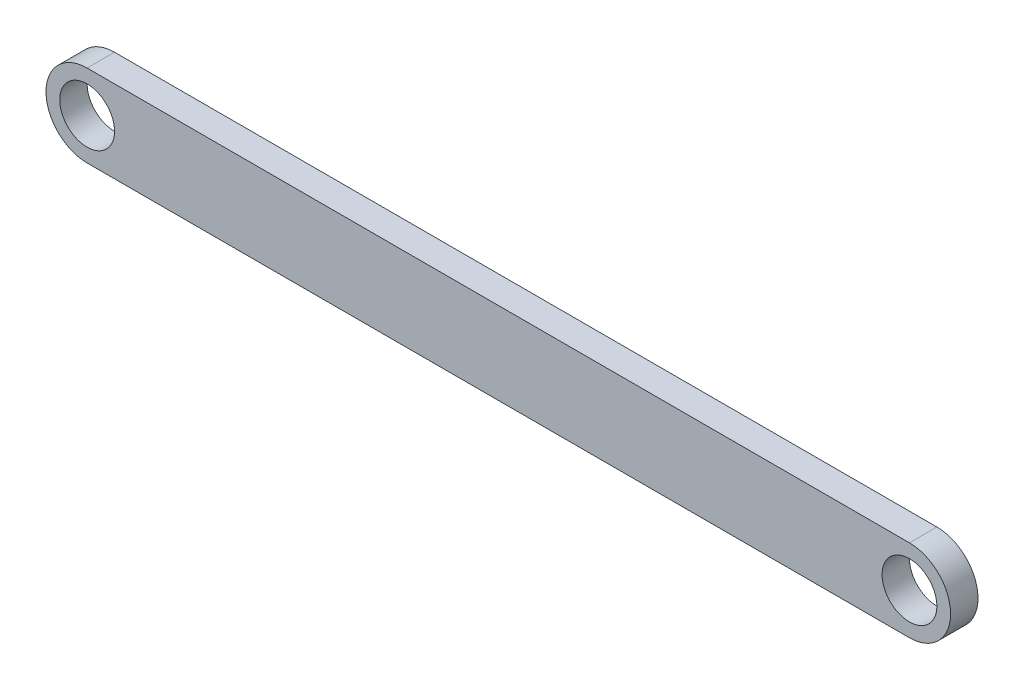
SolidWorks part; units mm, degrees
ref_plane "Ön Düzlem" through (0, 0, 0) normal (0, 0, 1) x (1, 0, 0)
ref_plane "Üst Düzlem" through (0, 0, 0) normal (0, 1, 0) x (1, 0, 0)
ref_plane "Sağ Düzlem" through (0, 0, 0) normal (1, 0, 0) x (0, 0, -1)
sketch "Çizim1" plane through (0, 0, 0) normal (0, 0, 1) x (1, 0, 0)
  line L0 (-43.2944, 9.8643) -> (106.7056, 9.8643) construction
  line L1 (-43.2944, 17.3643) -> (106.7056, 17.3643)
  line L2 (-43.2944, 2.3643) -> (106.7056, 2.3643)
  arc A0 (-43.2944, 17.3643) -> (-43.2944, 2.3643) centre (-43.2944, 9.8643) ccw
  arc A1 (106.7056, 2.3643) -> (106.7056, 17.3643) centre (106.7056, 9.8643) ccw
  circle A2 centre (-43.2944, 9.8643) radius 5
  circle A3 centre (106.7056, 9.8643) radius 5
  point P2 (31.7056, 9.8643)
extrude "Yükseklik-Ekstrüzyon1" add sketch "Çizim1" along normal blind 5
